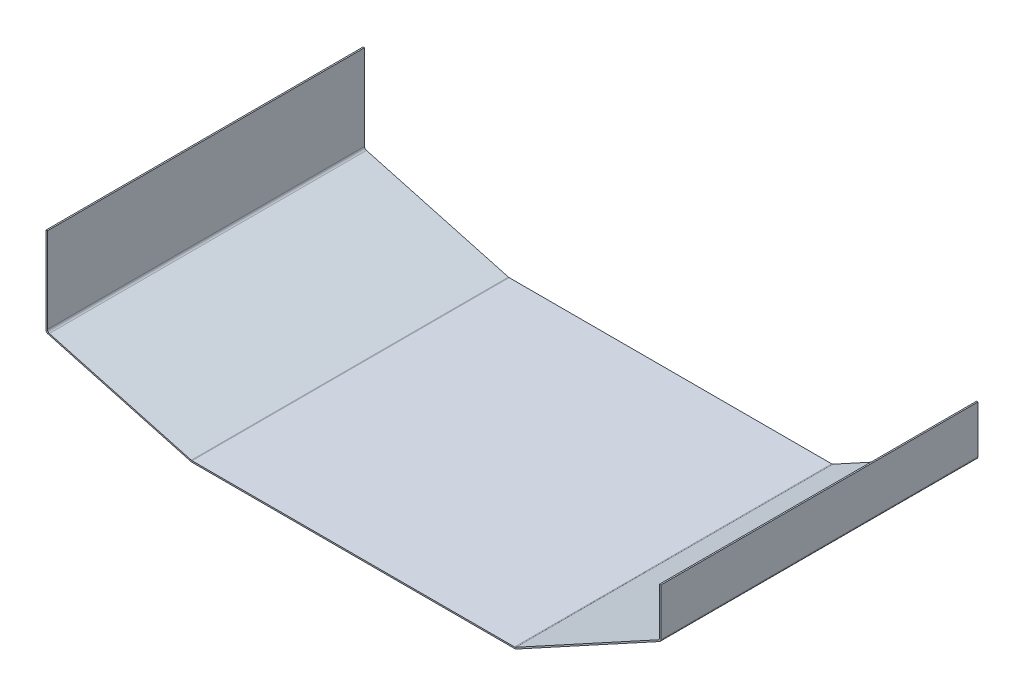
SolidWorks part; units mm, degrees
ref_plane "Front Plane" through (0, 0, 0) normal (0, 0, 1) x (1, 0, 0)
ref_plane "Top Plane" through (0, 0, 0) normal (0, 1, 0) x (1, 0, 0)
ref_plane "Right Plane" through (0, 0, 0) normal (1, 0, 0) x (0, 0, -1)
sketch "Sketch1" plane through (0, 0, 0) normal (0, 0, 1) x (1, 0, 0)
  line L0 (0, 0) -> (0, -100)
  line L1 (0, -100) -> (165, -145)
  line L2 (165, -145) -> (535, -145)
  line L3 (535, -145) -> (700, -55)
  line L4 (700, -55) -> (700, 0)
  line L5 (0, 0) -> (700, 0) construction
  dimension "D1" = 145
  dimension "D2" = 165
  dimension "D3" = 700
  dimension "D4" = 100
  dimension "D5" = 165
  dimension "D6" = 55
extrude "Extrude-Thin1" add sketch "Sketch1" along normal up to surface (362.7 mm away) thin
fillet "Fillet1" radius 3 8 edges at (700, -55, 181.35) (701.5875, -55.9424, 181.35) (535.4048, -146.5875, 181.35) (535, -145, 181.35) (165, -145, 181.35) (164.7874, -146.5875, 181.35) (-1.5875, -101.2125, 181.35) (0, -100, 181.35)
